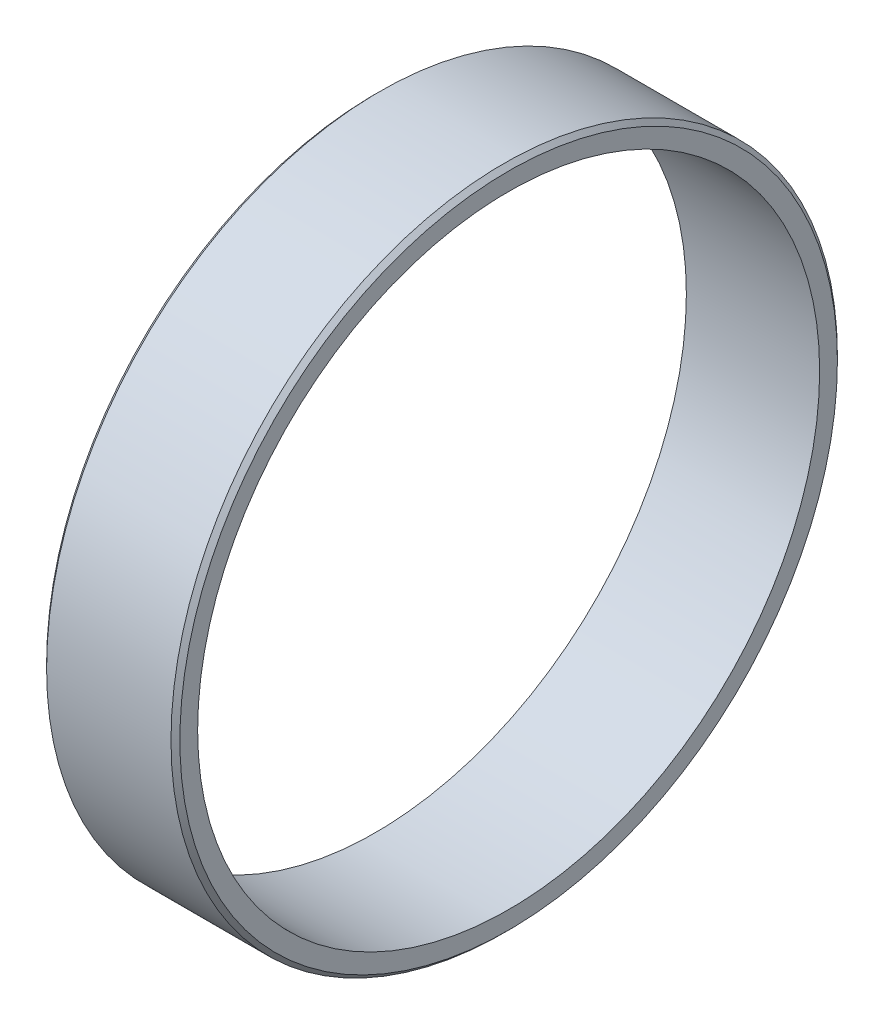
SolidWorks part; units mm, degrees
ref_plane "Front Plane" through (0, 0, 0) normal (0, 0, 1) x (1, 0, 0)
ref_plane "Top Plane" through (0, 0, 0) normal (0, 1, 0) x (1, 0, 0)
ref_plane "Right Plane" through (0, 0, 0) normal (1, 0, 0) x (0, 0, -1)
sketch "Sketch1" plane through (0, 0, 0) normal (0, 0, 1) x (1, 0, 0)
  line L0 (-29.3925, 0) -> (29.3925, 0) construction
  line L1 (-7.5, -35) -> (7.5, -35)
  line L2 (-7.5, -35) -> (-7.5, -37.5)
  line L3 (-7.5, -37.5) -> (7.5, -37.5)
  line L4 (7.5, -35) -> (7.5, -37.5)
  line L5 (-7.5, -35) -> (7.5, -37.5) construction
  line L6 (-7.5, -37.5) -> (7.5, -35) construction
  point P0 (0, -36.25)
  point P9 (0, 0)
  dimension "D1" = 70
  dimension "D2" = 75
  dimension "D3" = 15
revolve "Revolve1" add sketch "Sketch1" angle 360 about L0
chamfer "Chamfer1" distance 0.5 angle 45 2 edges at (-7.5, 0, 37.5) (7.5, 0, 37.5)
